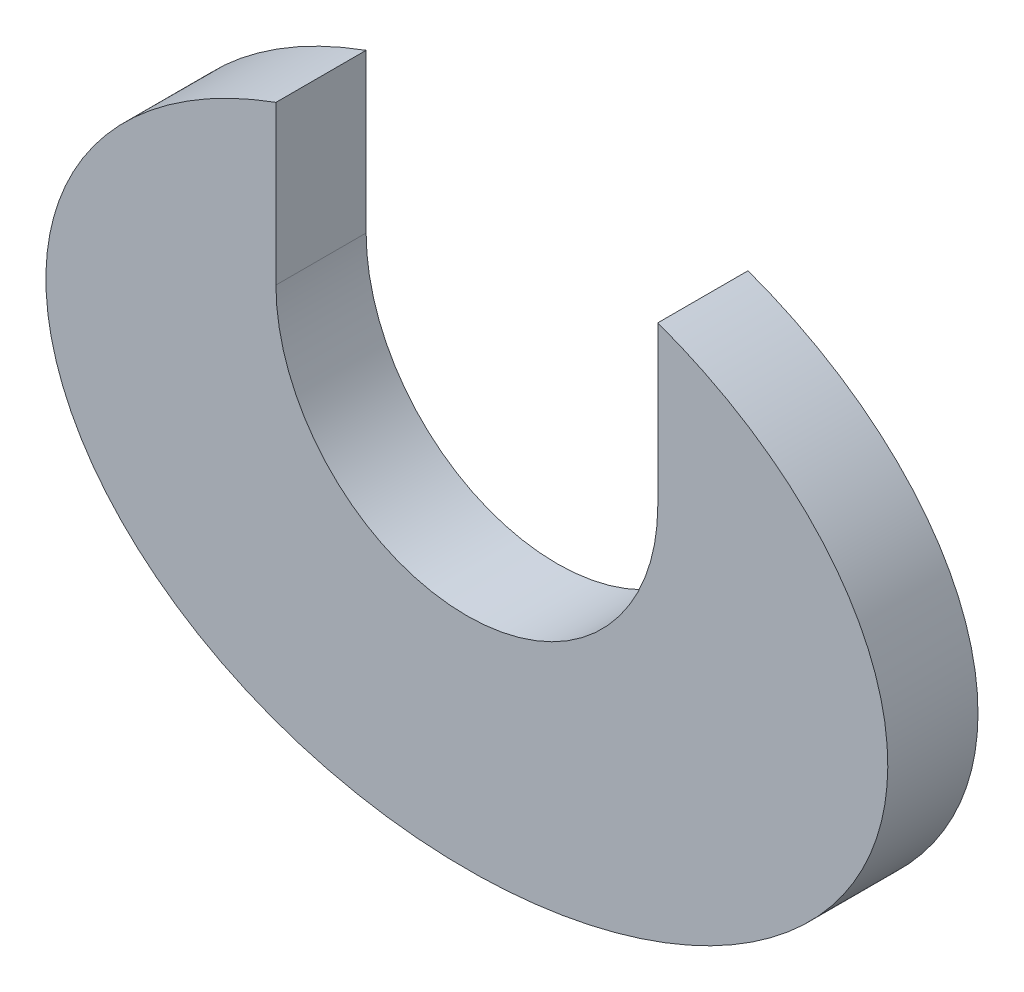
SolidWorks part; units mm, degrees
ref_plane "Front Plane" through (0, 0, 0) normal (0, 0, 1) x (1, 0, 0)
ref_plane "Top Plane" through (0, 0, 0) normal (0, 1, 0) x (1, 0, 0)
ref_plane "Right Plane" through (0, 0, 0) normal (1, 0, 0) x (0, 0, -1)
sketch "Sketch1" plane through (0, 0, 0) normal (0, 0, 1) x (1, 0, 0)
  ellipse E0 centre (0, 0) end of major axis (14, 0) minor radius 10
  point P1 (0, 0)
  dimension "D1" = 10
  dimension "D2" = 14
extrude "Ring extrude" add sketch "Sketch1" along normal mid plane 3
sketch "Sketch2" plane through (0, 0, 1.5) normal (0, 0, 1) x (1, 0, 0)
  line L2 (-6.35, 3.65) -> (-6.35, 8.9122)
  line L3 (6.35, 3.65) -> (6.35, 8.9122)
  arc A3 (-6.35, 3.65) -> (6.35, 3.65) centre (0, 3.65) ccw
  ellipse E0 centre (0, 0) end of major axis (14, 0) minor radius 10 construction
  ellipse E1 centre (0, 0) end of major axis (14, 0) minor radius 10 (6.35, 8.9122) -> (-6.35, 8.9122) ccw
  dimension "D1" = 12.7
extrude "Spar cut" cut sketch "Sketch2" against normal through all both and the other way through all
